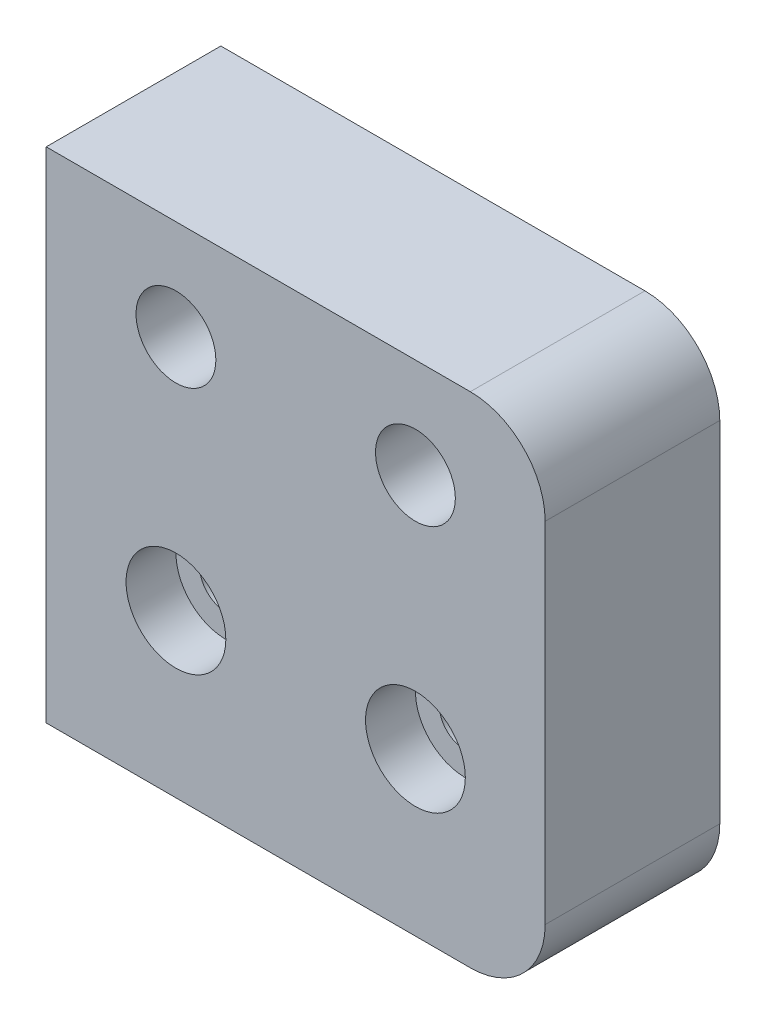
SolidWorks part; units mm, degrees
material "ABS"
ref_plane "Front Plane" through (0, 0, 0) normal (0, 0, 1) x (1, 0, 0)
ref_plane "Top Plane" through (0, 0, 0) normal (0, 1, 0) x (1, 0, 0)
ref_plane "Right Plane" through (0, 0, 0) normal (1, 0, 0) x (0, 0, -1)
sketch "Sketch1" plane through (0, 0, 0) normal (0, 0, 1) x (1, 0, 0)
  line L0 (0, 10) -> (20, 10) construction
  line L1 (0, 0) -> (17, 0)
  line L2 (0, 0) -> (0, 20)
  line L3 (0, 20) -> (17, 20)
  line L4 (20, 3) -> (20, 17)
  line L5 (10, 20) -> (10, 0) construction
  line L6 (5.2, 16) -> (14.8, 16) construction
  arc A0 (17, 0) -> (20, 3) centre (17, 3) ccw
  arc A1 (20, 17) -> (17, 20) centre (17, 17) ccw
  circle A2 centre (5.2, 16) radius 1.6
  circle A3 centre (14.8, 16) radius 1.6
  circle A4 centre (5.2, 6.5) radius 1.05
  circle A5 centre (14.8, 6.5) radius 1.05
  point P9 (20, 20)
  point P14 (10, 10)
  point P23 (10, 16)
  dimension "D3" = 3
  dimension "D4" = 9.6
  dimension "D5" = 3.2
  dimension "D6" = 6
  dimension "D7" = 2.1
  dimension "D8" = 3.5
  dimension "D1" = 20
  dimension "D2" = 20
extrude "Boss-Extrude1" add sketch "Sketch1" along normal blind 7
sketch "Sketch2" plane through (0, 0, 7) normal (0, 0, 1) x (1, 0, 0)
  circle A0 centre (5.2, 6.5) radius 2
  circle A1 centre (14.8, 6.5) radius 2
  dimension "D1" = 4
extrude "Cut-Extrude1" cut sketch "Sketch2" against normal blind 2
